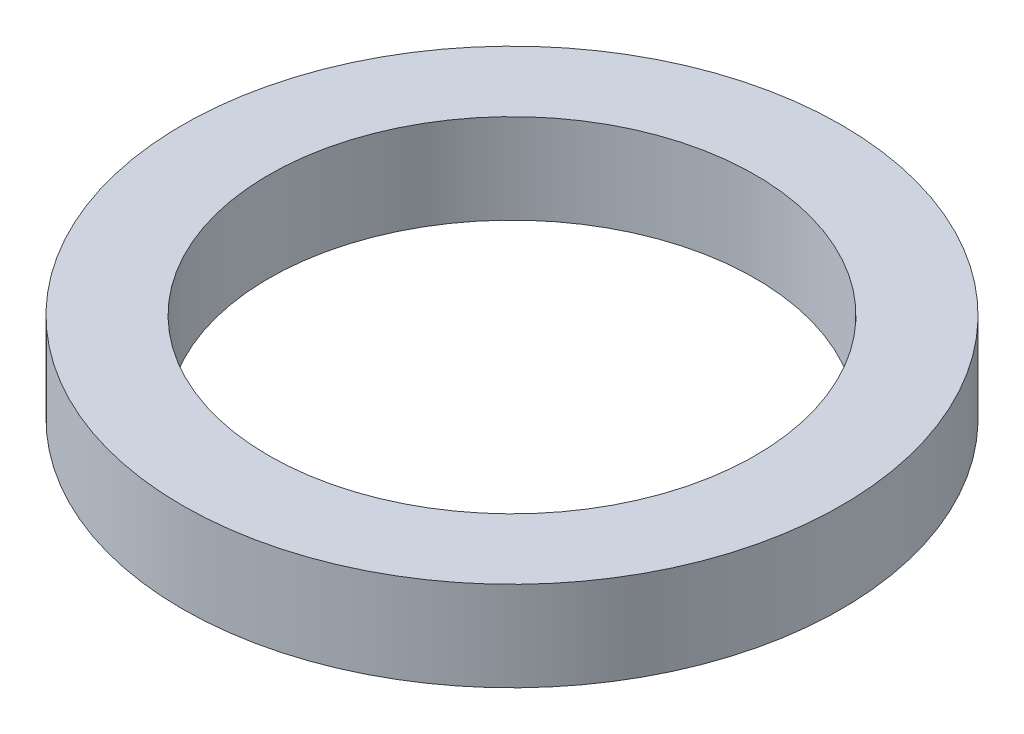
SolidWorks part; units mm, degrees
ref_plane "Front Plane" through (0, 0, 0) normal (0, 0, 1) x (1, 0, 0)
ref_plane "Top Plane" through (0, 0, 0) normal (0, 1, 0) x (1, 0, 0)
ref_plane "Right Plane" through (0, 0, 0) normal (1, 0, 0) x (0, 0, -1)
sketch "Sketch1" plane through (0, 0, 0) normal (0, 1, 0) x (1, 0, 0)
  circle A0 centre (0, 0) radius 24.5
  circle A1 centre (0, 0) radius 33.195
  dimension "D1" = 49
  dimension "D2" = 66.39
extrude "Boss-Extrude1" add sketch "Sketch1" along normal mid plane 9.03
equation "\"Nr\"= \"Ns\" + 2 * \"Np\"'num teeth"
equation "\"module\"= 0.65"
equation "\"pressure_angle\"= 20deg"
equation "\"h_a\"= 1 * \"module\"'addendum"
equation "\"h_f\"= 1.25 * \"module\"'dedendum"
equation "\"clr_tip_root\"= \"h_f\" - \"h_a\"'clearance of gear tooth tip and root"
equation "\"dp_r\"= \"module\" * \"Nr\"'PCD"
equation "\"db_r\"= \"dp_r\" * cos ( \"pressure_angle\" )'base CD"
equation "\"fw_r\"= 11.5mm'face width"
equation "\"alpha_r\"= sqr ( \"dp_r\" ^ 2 - \"db_r\" ^ 2 ) / \"db_r\" * 180 / pi - \"pressure_angle\""
equation "\"beta_r\"= ( 360 / ( 4 * \"Nr\" ) + \"alpha_r\" ) * 2"
equation "\"bearing_ID\"= \"module\" * ( \"Ns\" + \"Np\" ) + 10"
equation "\"bearing_OD\"= 1.18 * \"bearing_ID\" + 8.57"
equation "\"bearing_height\"= 0.09 * \"bearing_ID\" + 4.62"
equation "\"clearance_planet\"=1.5"
equation "\"case_dist\"= \"sec_carrier_thickness\" + \"clearance_planet\" + \"sun_coupler_hub_thickness\" - \"case_mounting_surface_height\""
equation "\"Motor_case_OD_max\"= \"case_mounting_PCD\" + \"case_mounting_hole_allen_socket_dia\" + \"clearance_case_mount_holes_shell_thickness\" * 2"
equation "\"case_mounting_PCD\"= \"motor_case_OD_base\" + \"case_mounting_hole_shift\" * 2"
equation "\"bearing mount thickness\"= \"output_mounting_hole_dia\" * 2"
equation "\"case_mounting_hole_dia\"=3"
equation "\"output_mounting_PCD\"= \"bearing_OD\" + \"bearing mount thickness\""
equation "\"output_mounting_hole_dia\"= 4"
equation "\"clearance_case_mount_holes_shell_thickness\"= 1"
equation "\"motor_case_OD_base\"= \"motor_OD\" + \"clearance_motor_and_case\" * 2 + \"Motor_case_thickness\" * 2"
equation "\"sec_carrier_thickness\"= 5"
equation "\"sun_coupler_hub_thickness\"= 4"
equation "\"clearance_sun_coupler_sec_carrier\"= 1.5"
equation "\"clearance_motor_and_case\"= 2.2"
equation "\"motor_OD\"= 72"
equation "\"Motor_case_thickness\"= 2"
equation "\"Motor_case_ID\"= \"motor_OD\" + \"clearance_motor_and_case\" * 2"
equation "\"case_mounting_hole_shift\"= \"case_mounting_hole_dia\" / 2 - 0.5"
equation "\"output_mounting_nut_wrench_size\"= 7"
equation "\"output_mounting_nut_thickness\"= 3.2"
equation "\"case_mounting_hole_allen_socket_dia\"= 5.5"
equation "\"output_mounting_nut_depth\"= 3"
equation "\"case_mounting_bolt_depth\"= 4.5"
equation "\"Ns\"= 20"
equation "\"Np\"= 40"
equation "\"ring_radial_thickness\"= 5"
equation "\"ring_OD\"= \"Nr\" * \"module\" + \"ring_radial_thickness\" * 2"
equation "\"ring_to_chamfer_clearance\"= 2"
equation "\"Motor_case_OD_base_to_chamfer\"=5"
equation "\"pattern_offset_from_motor_case_OD_base\"= 3"
equation "\"pattern_bulge_dia\"= 3"
equation "\"pattern_num_bulge\"= 18"
equation "\"pattern_depth\"= 2"
equation "\"motor_height\"= 27"
equation "\"case_mounting_wrench_size\"= 5.5"
equation "\"case_mounting_nut_clearance\"= 2"
equation "\"base_plate_thickness\"= 4"
equation "\"case_mounting_nut_thickness\"= 2.4"
equation "\"case_mounting_surface_height\"= 4"
equation "\"motor_mount_hole_PCD\"= 32"
equation "\"motor_mount_hole_dia\"= 4"
equation "\"motor_mount_hole_num\"= 4"
equation "\"central_hole_offset_from_motor_mount_PCD\"= 5"
equation "\"wire_slot_dist_from_center\"= 30"
equation "\"wire_slot_length\"= 10"
equation "\"wire_slot_radius\"= 4"
equation "\"driver_upper_holes_dist_from_center\"= 23"
equation "\"driver_lower_holes_dist_from_center\"= 15"
equation "\"driver_side_holes_dist_from_center\"= 20"
equation "\"driver_mount_holes_dia\"= 2.5"
equation "\"driver_mount_inserts_OD\"= 3.5"
equation "\"driver_mount_thickness\"= 1.5"
equation "\"driver_mount_height\"= 4"
equation "\"air_flow_hole_offset\"= 3"
equation "\"num_planet\"= 3"
equation "\"planet_pin_bolt_dia\"= 5"
equation "\"planet_pin_socket_head_dia\"= 8.5"
equation "\"carrier_PCD\"= ( \"Np\" + \"Ns\" ) * \"module\""
equation "\"planet_shaft_dia\"= 8"
equation "\"fw_p\"= \"fw_r\""
equation "\"planet_shaft_step_offset\"= 1"
equation "\"carrier_trapezoidal_support_sun_offset\"= 5"
equation "\"carrier_trapezoidal_support_hole_PCD_offset_bearing_ID\"= 4"
equation "\"carrier_trapezoidal_support_hole_dia\"= 3"
equation "\"carrier_trapezoidal_support_hole_socket_head_dia\"= 5.5"
equation "\"carrier_bearing_step_width\"= 1.5"
equation "\"standard_clearance_1_5mm\"=1.5"
equation "\"standard_fillet_1_5mm\"= 1.5"
equation "\"sun_shaft_bearing_OD\"= 16"
equation "\"sun_shaft_bearing_width\"= 4"
equation "\"standard_bearing_insertion_chamfer\"= 0.5"
equation "\"D1@Sketch1\"=\"bearing_ID\""
equation "\"D2@Sketch1\"=\"bearing_OD\""
equation "\"D1@Boss-Extrude1\"=\"bearing_height\""
equation "\"D7@Sketch2\"=\"carrier_trapezoidal_support_hole_dia\""
equation "\"D5@Sketch2\"= 360 / ( 4 * \"Ns\" ) - \"alpha_s\""
equation "\"D3@Sketch2\"=\"dp_s\"- 2*\"h_b\""
equation "\"D9@Sketch2\"=\"carrier_trapezoidal_support_sun_offset\""
equation "\"carrier_trapezoidal_support_hole_wrench_size\"= 5.5"
equation "\"planet_pin_bolt_wrench_size\"= 8"
